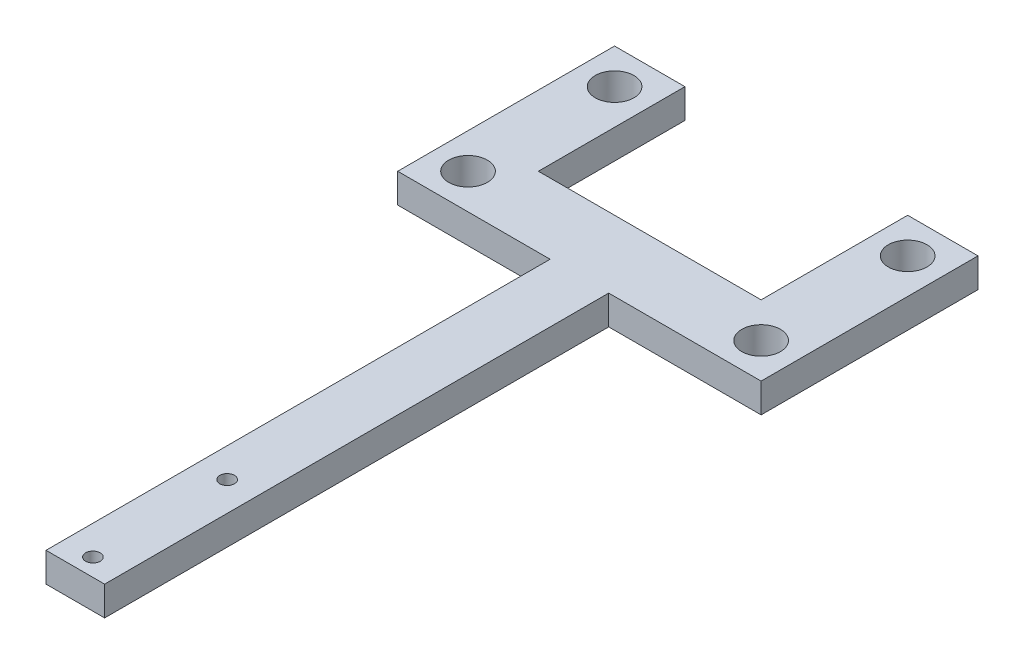
SolidWorks part; units mm, degrees
ref_plane "Front Plane" through (0, 0, 0) normal (0, 0, 1) x (1, 0, 0)
ref_plane "Top Plane" through (0, 0, 0) normal (0, 1, 0) x (1, 0, 0)
ref_plane "Right Plane" through (0, 0, 0) normal (1, 0, 0) x (0, 0, -1)
sketch "Sketch1" plane through (0, 0, 0) normal (0, 1, 0) x (1, 0, 0)
  line L1 (-31, -61.5) -> (31, -61.5)
  line L2 (-31, -61.5) -> (-31, 61.5)
  line L3 (-31, 61.5) -> (31, 61.5)
  line L4 (31, -61.5) -> (31, 61.5)
  line L5 (-31, -61.5) -> (31, 61.5) construction
  line L6 (-31, 61.5) -> (31, -61.5) construction
  point P0 (0, 0)
  dimension "D1" = 123
  dimension "D2" = 62
extrude "Extrude1" add sketch "Sketch1" along normal blind 5
sketch "Sketch2" plane through (0, 0, -61.5) normal (0, 0, -1) x (-1, 0, 0)
  line L0 (-31, 5) -> (31, 5) construction
  line L1 (-19, 5) -> (19, 5)
  line L2 (-19, 5) -> (-19, 0)
  line L3 (-19, 0) -> (19, 0)
  line L4 (19, 5) -> (19, 0)
  line L5 (-31, 0) -> (31, 0) construction
  dimension "D1" = 19
  dimension "D2" = 19
extrude "Extrude2" cut sketch "Sketch2" against normal blind 25
sketch "Sketch3" plane through (-31, 0, 0) normal (-1, 0, 0) x (0, 0, 1)
  line L0 (-61.5, 5) -> (61.5, 5) construction
  line L1 (61.5, 0) -> (-24.5, 0)
  line L2 (61.5, 0) -> (61.5, 5)
  line L3 (61.5, 5) -> (-24.5, 5)
  line L4 (-24.5, 0) -> (-24.5, 5)
  dimension "D1" = 86
extrude "Extrude3" cut sketch "Sketch3" against normal blind 26
sketch "Sketch4" plane through (31, 0, 0) normal (1, 0, 0) x (0, 0, -1)
  line L0 (-61.5, 5) -> (61.5, 5) construction
  line L1 (-61.5, 0) -> (24.5, 0)
  line L2 (-61.5, 0) -> (-61.5, 5)
  line L3 (-61.5, 5) -> (24.5, 5)
  line L4 (24.5, 0) -> (24.5, 5)
  dimension "D1" = 86
extrude "Extrude4" cut sketch "Sketch4" against normal blind 26
hole_wizard "M6 Clearance Hole1" positions "3DSketch1" profile "Sketch6" hole size "M6" standard "Ansi Metric"
sketch3d "3DSketch1"
  line L0 (-31, 5, -61.5) -> (-31, 5, -24.5) construction
  line L1 (-19, 5, -61.5) -> (-31, 5, -61.5) construction
  point P0 (-25, 5, -55.5)
  dimension "D1" = 6
  dimension "D2" = 6
sketch "Sketch6" plane through (-25, 5, -55.5) normal (1, 0, 0) x (0, 0, 1)
  line L0 (0, 0) -> (0, 11.9828)
  line L1 (0, 11.9828) -> (3.3, 10)
  line L2 (3.3, 10) -> (3.3, 0)
  line L5 (3.3, 0) -> (0, 0)
  line L10 (0, 11.9828) -> (-3.3, 10) construction
  line L11 (0, -6.35) -> (0, 107.95) construction
  dimension "Hole Dia." = 6.6
  dimension "Hole Depth" = 10
  dimension "Drill Angle" = 118
sketch "Sketch7" plane through (0, 5, 0) normal (0, 1, 0) x (-1, 0, 0)
  line L0 (0, -79.0047) -> (0, 74.1241) construction
  line L1 (48.5993, 0) -> (-53.4865, 0) construction
pattern_linear "LPattern1" count 2 spacing 25 along (0, 0, 1) count 2 spacing 50 along (1, 0, 0) of "M6 Clearance Hole1"
hole_wizard "M3x0.5 Tapped Hole1" positions "3DSketch2" profile "Sketch8" tap size "M3x0.5" standard "Ansi Metric" end condition through all
sketch3d "3DSketch2"
  line L0 (0, 5, -79.0047) -> (0, 5, 74.1241) construction
  line L1 (-5, 5, 61.5) -> (5, 5, 61.5) construction
  point P0 (0, 5, 58.5)
  dimension "D1" = 3
sketch "Sketch8" plane through (0, 5, 58.5) normal (1, 0, 0) x (0, 0, 1)
  line L0 (0, 0) -> (0, 5)
  line L1 (0, 5) -> (1.25, 5)
  line L2 (1.25, 5) -> (1.25, 0)
  line L5 (1.25, 0) -> (0, 0)
  line L11 (0, -6.35) -> (0, 107.95) construction
  dimension "Thread Major Dia." = 2.5
  dimension "Thru Tap Drill Depth" = 5
pattern_linear "LPattern2" count 2 spacing 22.9 along (0, 0, -1) of "M3x0.5 Tapped Hole1"
